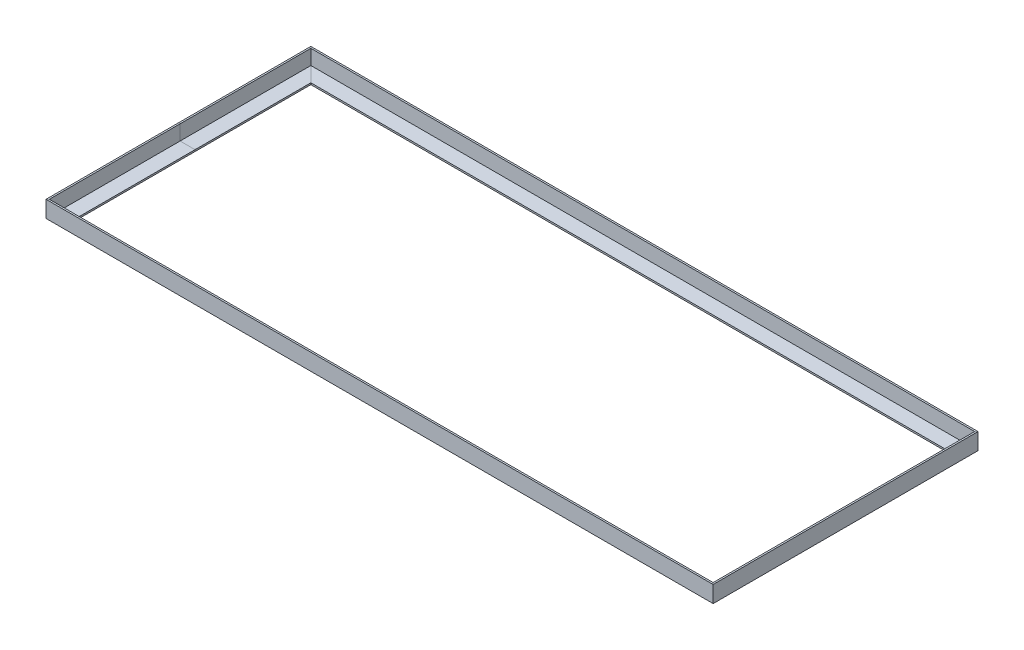
SolidWorks part; units mm, degrees
ref_plane "Front Plane" through (0, 0, 0) normal (0, 0, 1) x (1, 0, 0)
ref_plane "Top Plane" through (0, 0, 0) normal (0, 1, 0) x (1, 0, 0)
ref_plane "Right Plane" through (0, 0, 0) normal (1, 0, 0) x (0, 0, -1)
sketch "Sketch2" plane through (0, 0, 0) normal (0, 1, 0) x (1, 0, 0)
  line L1 (-1005, -399) -> (1005, -399)
  line L2 (-1005, -399) -> (-1005, 399)
  line L3 (-1005, 399) -> (1005, 399)
  line L4 (1005, -399) -> (1005, 399)
  line L5 (-1005, -399) -> (1005, 399) construction
  line L6 (-1005, 399) -> (1005, -399) construction
  point P0 (0, 0)
  dimension "D1" = 798
  dimension "D2" = 2010
sketch "Sketch3" plane through (0, 0, 0) normal (0, 0, 1) x (1, 0, 0)
  line L0 (-955, 0) -> (-1005, 0)
  line L1 (-1005, 0) -> (1005, 0) construction
  line L2 (-1005, 0) -> (1005, 0) construction
  line L3 (-1005, 0) -> (-1005, 50)
  line L4 (-1005, 50) -> (-1000, 50)
  line L5 (-1000, 50) -> (-1000, 5)
  line L6 (-1000, 5) -> (-955, 5)
  line L7 (-955, 5) -> (-955, 0)
  dimension "D1" = 50
  dimension "D2" = 50
  dimension "D3" = 5
  dimension "D4" = 5
sweep "Sweep1" add profiles "Sketch3" path "Sketch2"
